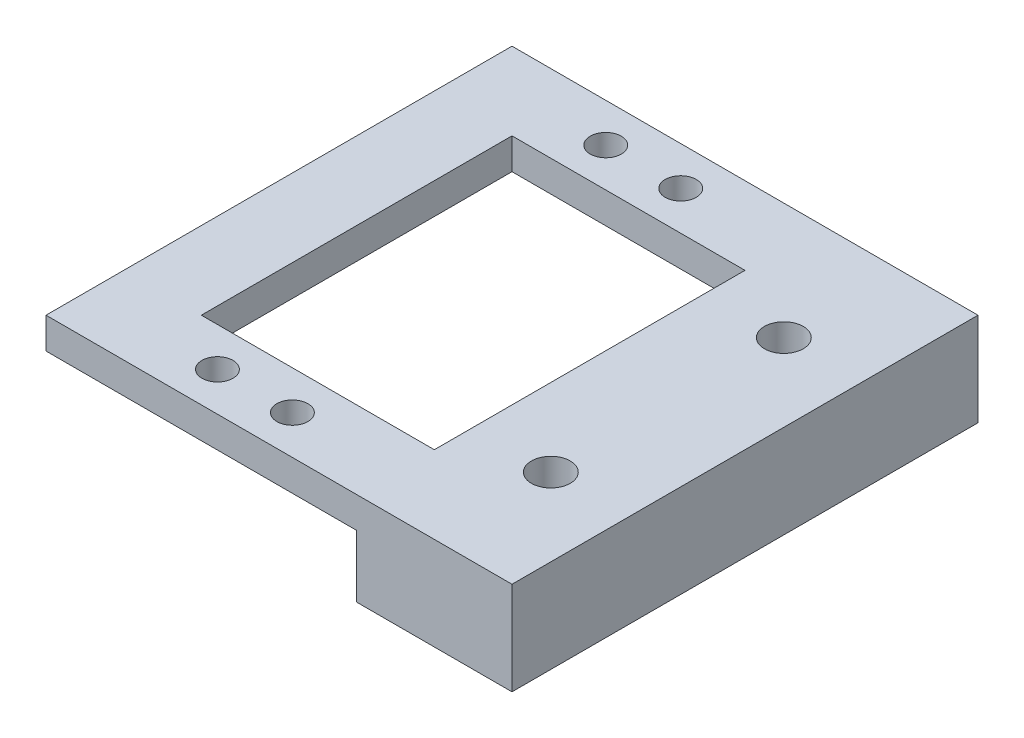
SolidWorks part; units mm, degrees
material "ABS"
ref_plane "前视基准面" through (0, 0, 0) normal (0, 0, 1) x (1, 0, 0)
ref_plane "上视基准面" through (0, 0, 0) normal (0, 1, 0) x (1, 0, 0)
ref_plane "右视基准面" through (0, 0, 0) normal (1, 0, 0) x (0, 0, -1)
other "Configuration Table"
sketch "草图1" plane through (0, 0, 0) normal (0, 1, 0) x (1, 0, 0)
  line L1 (-10, 30) -> (10, 30)
  line L2 (-10, 30) -> (-10, -30)
  line L3 (-10, -30) -> (10, -30)
  line L4 (10, 30) -> (10, -30)
  line L5 (-10, 30) -> (10, -30) construction
  line L6 (-10, -30) -> (10, 30) construction
  point P0 (0, 0)
  dimension "D1" = 20
  dimension "D2" = 60
extrude "凸台-拉伸1" add sketch "草图1" along normal blind 8
sketch "草图3" plane through (0, 8, 0) normal (0, 1, 0) x (1, 0, 0)
  line L1 (10, -30) -> (-50, -30)
  line L2 (10, -30) -> (10, -20)
  line L3 (10, -20) -> (-50, -20)
  line L4 (-50, -30) -> (-50, -20)
  line L5 (0, 0) -> (-69.6622, 0) construction
  line L6 (-50, 30) -> (-50, 20)
  line L7 (10, 20) -> (-50, 20)
  line L8 (10, 30) -> (10, 20)
  line L9 (10, 30) -> (-50, 30)
  line L10 (-10, -30) -> (10, -30) construction
  line L15 (10, -30) -> (10, 30)
  line L16 (10, 30) -> (-10, 30)
  line L17 (-10, 30) -> (-10, -30)
  line L18 (-10, -30) -> (10, -30)
  line L19 (10, -30) -> (10, 30)
  line L20 (10, 30) -> (-10, 30)
  line L21 (-10, 30) -> (-10, -30)
  line L22 (-10, -30) -> (10, -30)
  dimension "D1" = 60
  dimension "D2" = 40
  dimension "D3" = 0
extrude "凸台-拉伸2" add sketch "草图3" along normal blind 4
sketch "草图4" plane through (0, 12, 0) normal (0, 1, 0) x (1, 0, 0)
  line L0 (-50, -30) -> (-50, 30)
  line L1 (10, 30) -> (-50, 30) construction
  line L2 (-50, 30) -> (-40, 30)
  line L3 (-40, 30) -> (-40, -30)
  line L4 (-50, -30) -> (10, -30) construction
  line L5 (-40, -30) -> (-50, -30)
  dimension "D1" = 10
extrude "凸台-拉伸3" add sketch "草图4" against normal blind 4
sketch "草图5" plane through (0, 12, 0) normal (0, 1, 0) x (1, 0, 0)
  line L0 (0, 28.1997) -> (0, -39.7052) construction
  line L2 (10, 30) -> (-50, 30) construction
  circle A0 centre (0, 15) radius 2.5
  circle A1 centre (0, -15) radius 2.5
  dimension "D1" = 5
  dimension "D2" = 5
  dimension "D3" = 30
  dimension "D4" = 15
extrude "切除-拉伸1" cut sketch "草图5" against normal blind 67
sketch "草图7" plane through (0, 8, 0) normal (0, -1, 0) x (1, 0, 0)
  arc A0 (-30.925, -25) -> (-34.925, -25) centre (-32.925, -25) ccw construction
  arc A1 (-30.925, -25) -> (-34.925, -25) centre (-32.925, -25) ccw
  arc A2 (-34.925, 25) -> (-30.925, 25) centre (-32.925, 25) ccw construction
  arc A3 (-25.275, 25) -> (-21.275, 25) centre (-23.275, 25) ccw construction
  arc A4 (-21.275, -25) -> (-25.275, -25) centre (-23.275, -25) ccw construction
  arc A5 (-34.925, 25) -> (-30.925, 25) centre (-32.925, 25) ccw
  arc A6 (-25.275, 25) -> (-21.275, 25) centre (-23.275, 25) ccw
  arc A7 (-21.275, -25) -> (-25.275, -25) centre (-23.275, -25) ccw
  circle A8 centre (-23.275, -25) radius 2
  circle A9 centre (-32.925, -25) radius 2
  circle A10 centre (-23.275, 25) radius 2
  circle A11 centre (-32.925, 25) radius 2
extrude "切除-拉伸2" cut sketch "草图7" against normal blind 10 contours A6 A10 | A5 A11 | A7 A8 | A1 A9
